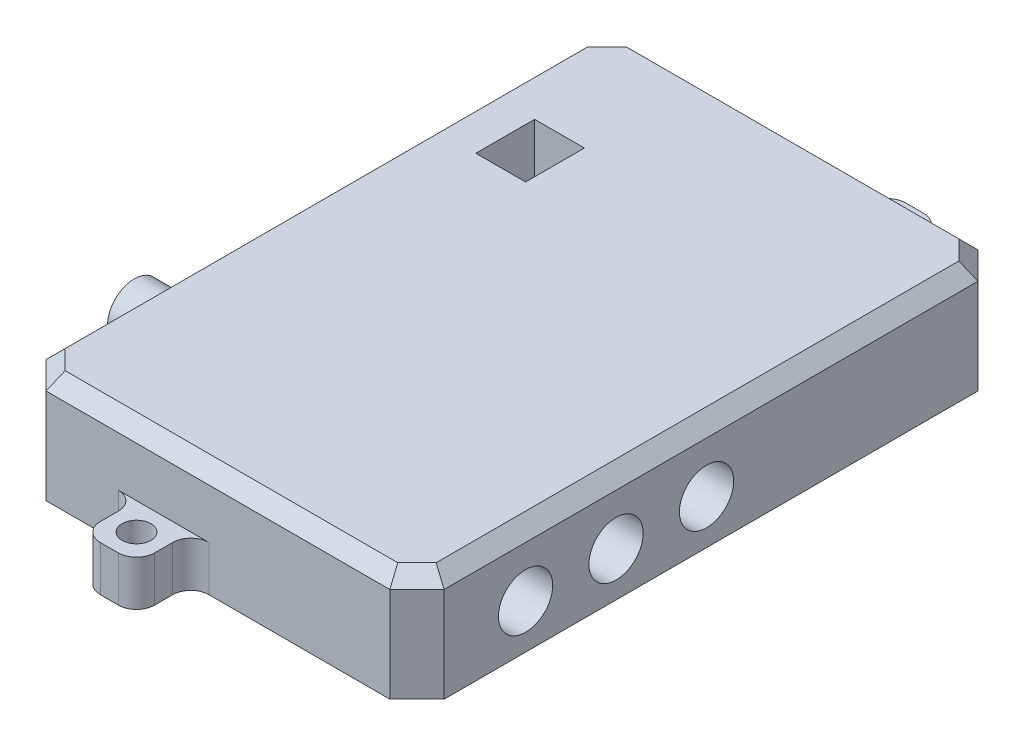
SolidWorks part; units mm, degrees
ref_plane "前视" through (0, 0, 0) normal (0, 0, 1) x (1, 0, 0)
ref_plane "上视" through (0, 0, 0) normal (0, 1, 0) x (1, 0, 0)
ref_plane "右视" through (0, 0, 0) normal (1, 0, 0) x (0, 0, -1)
sketch "草图1" plane through (0, 0, 0) normal (0, 1, 0) x (1, 0, 0)
  line L1 (-22, 32.5) -> (22, 32.5)
  line L2 (-22, 32.5) -> (-22, -32.5)
  line L3 (-22, -32.5) -> (22, -32.5)
  line L4 (22, 32.5) -> (22, -32.5)
  line L5 (-22, 32.5) -> (22, -32.5) construction
  line L6 (-22, -32.5) -> (22, 32.5) construction
  point P0 (0, 0)
  dimension "D1" = 65
  dimension "D2" = 44
extrude "凸台-拉伸1" add sketch "草图1" along normal blind 12
chamfer "倒角1" distance 3 angle 45 4 edges at (-22, 6, -32.5) (22, 6, -32.5) (22, 6, 32.5) (-22, 6, 32.5)
chamfer "倒角2" distance 1.5 angle 45 8 edges at (20.5, 12, -31) (22, 12, 0) (20.5, 12, 31) (0, 12, 32.5) (-20.5, 12, 31) (-22, 12, 0) (-20.5, 12, -31) (0, 12, -32.5)
sketch "草图2" plane through (0, 0, 0) normal (0, -1, 0) x (1, 0, 0)
  line L0 (-19, 32.5) -> (19, 32.5) construction
  line L1 (-9, 32.5) -> (-3, 32.5)
  line L2 (-9, 32.5) -> (-9, 38.5)
  line L3 (-9, 38.5) -> (-3, 38.5)
  line L4 (-3, 32.5) -> (-3, 38.5)
  line L5 (19, -32.5) -> (-19, -32.5) construction
  line L6 (3, -32.5) -> (9, -32.5)
  line L7 (3, -32.5) -> (3, -38.5)
  line L8 (3, -38.5) -> (9, -38.5)
  line L9 (9, -32.5) -> (9, -38.5)
  line L10 (-22, -29.5) -> (-22, 29.5) construction
  line L11 (22, 29.5) -> (22, -29.5) construction
  line L12 (-6, 38.5) -> (-6, 32.5) construction
  line L13 (6, -38.5) -> (6, -32.5) construction
  circle A0 centre (-6, 35.5) radius 1.6
  circle A1 centre (6, -35.5) radius 1.6
  dimension "D7" = 3.2
  dimension "D1" = 6
  dimension "D2" = 6
  dimension "D3" = 6
  dimension "D4" = 6
  dimension "D5" = 13
  dimension "D6" = 13
extrude "凸台-拉伸2" add sketch "草图2" against normal blind 5
fillet "圆角1" radius 2 4 edges
fillet "圆角2" radius 2 4 edges at (9, 2.5, -38.5) (3, 2.5, -38.5) (-3, 2.5, 38.5) (-9, 2.5, 38.5)
sketch "草图3" plane through (22, 0, 0) normal (1, 0, 0) x (0, 0, -1)
  line L0 (-32.5, 0) -> (-32.5, 10.5) construction
  circle A0 centre (-20.5, 4.9007) radius 3
  circle A1 centre (-10.5, 4.9007) radius 3
  circle A2 centre (-0.5, 4.9007) radius 3
  dimension "D1" = 6
  dimension "D2" = 12
  dimension "D3" = 10
  dimension "D4" = 10
extrude "切除-拉伸1" cut sketch "草图3" against normal blind 5
sketch "草图4" plane through (-22, 0, 0) normal (-1, 0, 0) x (0, 0, 1)
  circle A0 centre (14.7386, 5.3893) radius 2.964
extrude "凸台-拉伸3" add sketch "草图4" along normal blind 5
sketch "草图5" plane through (0, 0, 0) normal (0, -1, 0) x (1, 0, 0)
  line L0 (1, -32.5) -> (-19, -32.5) construction
  line L1 (-16.5, -19) -> (-11, -19)
  line L2 (-16.5, -19) -> (-16.5, -12.5)
  line L3 (-16.5, -12.5) -> (-11, -12.5)
  line L4 (-11, -19) -> (-11, -12.5)
  line L5 (-22, -29.5) -> (-22, 29.5) construction
  dimension "D1" = 13.5
  dimension "D2" = 20
  dimension "D3" = 5.5
  dimension "D4" = 11
extrude "切除-拉伸2" cut sketch "草图5" against normal through all
